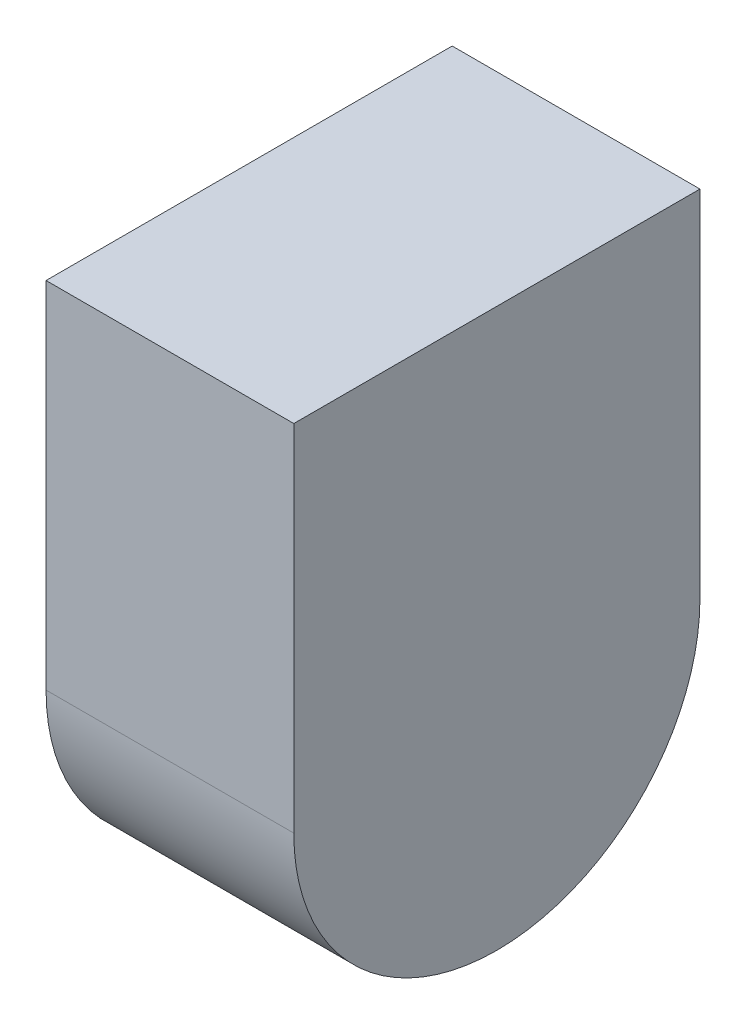
SolidWorks part; units mm, degrees
material "PA 类型 6"
ref_plane "前视基准面" through (0, 0, 0) normal (0, 0, 1) x (1, 0, 0)
ref_plane "上视基准面" through (0, 0, 0) normal (0, 1, 0) x (1, 0, 0)
ref_plane "右视基准面" through (0, 0, 0) normal (1, 0, 0) x (0, 0, -1)
sketch "草图1" plane through (0, 0, 0) normal (1, 0, 0) x (0, 0, -1)
  line L0 (15, 0) -> (15, 26.2)
  line L1 (15, 26.2) -> (-15, 26.2)
  line L2 (-15, 26.2) -> (-15, 0)
  arc A0 (-15, 0) -> (15, 0) centre (0, 0) ccw
  dimension "D1" = 30
  dimension "D2" = 26.2
extrude "凸台-拉伸1" add sketch "草图1" along normal blind 1
sketch "草图2" plane through (1, 0, 0) normal (1, 0, 0) x (0, 0, -1)
  line L3 (15, 0) -> (15, 26.2)
  line L4 (15, 26.2) -> (-15, 26.2)
  line L5 (-15, 26.2) -> (-15, 0)
  line L6 (15, 0) -> (15, 26.2)
  line L7 (15, 26.2) -> (-15, 26.2)
  line L8 (-15, 26.2) -> (-15, 0)
  line L12 (14, 0) -> (14, 25.2)
  line L13 (14, 25.2) -> (-14, 25.2)
  line L14 (-14, 25.2) -> (-14, 0)
  line L15 (14, 0) -> (14, 25.2)
  line L16 (14, 25.2) -> (-14, 25.2)
  line L17 (-14, 25.2) -> (-14, 0)
  arc A1 (-15, 0) -> (15, 0) centre (0, 0) ccw
  arc A2 (-15, 0) -> (15, 0) centre (0, 0) ccw
  arc A4 (-14, 0) -> (14, 0) centre (0, 0) ccw
  arc A5 (-14, 0) -> (14, 0) centre (0, 0) ccw
  dimension "D1" = 0
  dimension "D2" = 1
extrude "凸台-拉伸2" add sketch "草图2" along normal blind 14.6
ref_plane "基准面1" through (3.6, 0, 0) normal (1, 0, 0) x (0, 0, -1)
sketch "草图4" plane through (3.6, 0, 0) normal (1, 0, 0) x (0, 0, -1)
  line L0 (14, 25.2) -> (14, 20.2)
  line L1 (14, 0) -> (14, 25.2) construction
  line L2 (14, 20.2) -> (-14, 20.2)
  line L3 (-14, 25.2) -> (-14, 0) construction
  line L4 (-14, 20.2) -> (-14, 14.2)
  line L5 (-14, 25.2) -> (-14, 0) construction
  line L6 (-14, 14.2) -> (-8.5, 8.7)
  line L7 (-8.5, 8.7) -> (8.5, 8.7)
  line L8 (8.5, 8.7) -> (14, 14.2)
  line L9 (14, 14.2) -> (14, 20.2)
  dimension "D1" = 5
  dimension "D2" = 6
  dimension "D3" = 6
  dimension "D4" = 11.5
extrude "凸台-拉伸3" add sketch "草图4" along normal blind 6 contours L8 L9 L2 L4 L6 L7
ref_plane "基准面2" through (14.6, 0, 0) normal (1, 0, 0) x (0, 0, -1)
sketch "草图5" plane through (14.6, 0, 0) normal (1, 0, 0) x (0, 0, -1)
  line L0 (14, 14.2) -> (14, 20.2)
  line L1 (14, 20.2) -> (-14, 20.2)
  line L2 (-14, 20.2) -> (-14, 14.2)
  line L3 (-14, 14.2) -> (-8.5, 8.7)
  line L4 (-8.5, 8.7) -> (8.5, 8.7)
  line L5 (8.5, 8.7) -> (14, 14.2)
extrude "凸台-拉伸4" add sketch "草图5" against normal blind 2.5
sketch "草图6" plane through (15.6, 0, 0) normal (1, 0, 0) x (0, 0, -1)
  line L1 (-15, 0) -> (-15, 26.2)
  line L3 (15, 0) -> (15, 26.2)
  line L4 (15, 26.2) -> (-15, 26.2)
  line L5 (-15, 26.2) -> (-15, 0)
  line L6 (15, 0) -> (15, 26.2)
  line L7 (15, 26.2) -> (-15, 26.2)
  arc A1 (-15, 0) -> (15, 0) centre (0, 0) ccw
  arc A2 (-15, 0) -> (15, 0) centre (0, 0) ccw
  dimension "D1" = 0
extrude "凸台-拉伸6" add sketch "草图6" along normal blind 2.7
